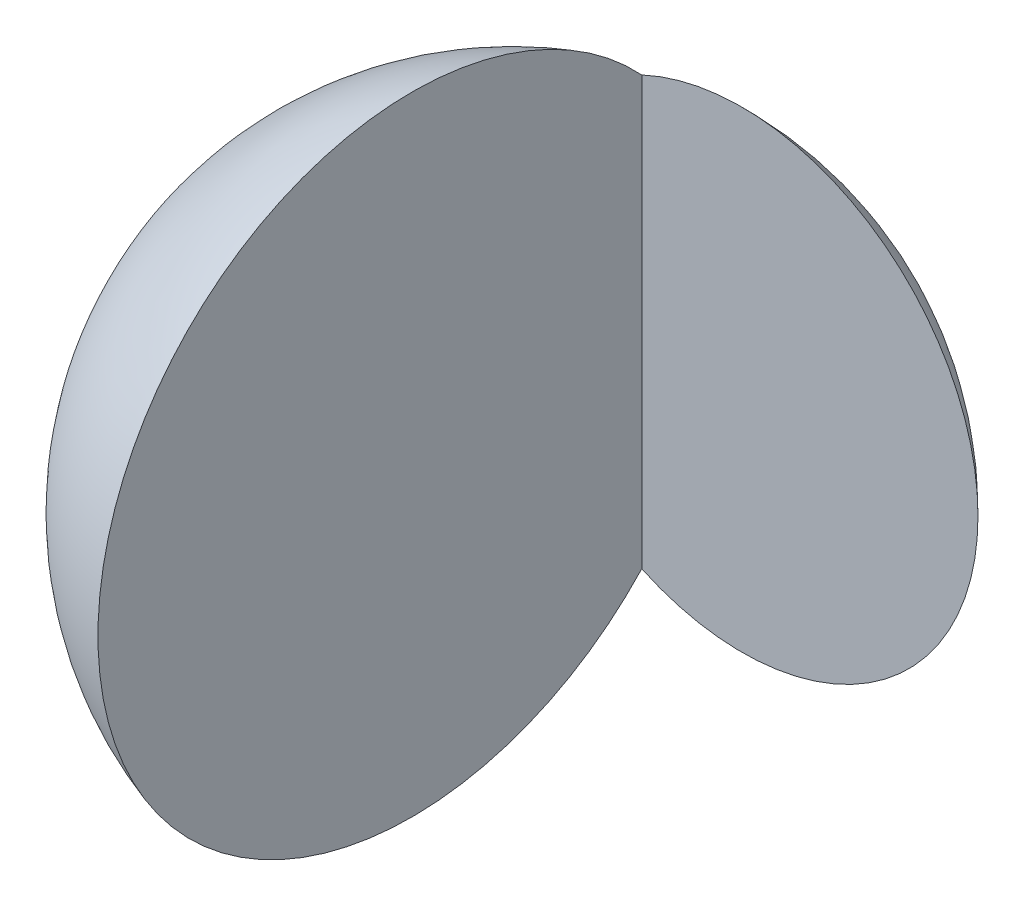
SolidWorks part; units mm, degrees
ref_plane "Front Plane" through (0, 0, 0) normal (0, 0, 1) x (1, 0, 0)
ref_plane "Top Plane" through (0, 0, 0) normal (0, 1, 0) x (1, 0, 0)
ref_plane "Right Plane" through (0, 0, 0) normal (1, 0, 0) x (0, 0, -1)
sketch "Sketch1" plane through (0, 0, 0) normal (0, 1, 0) x (1, 0, 0)
  line L0 (-27.6247, 0) -> (27.6247, 0)
  arc A0 (-27.6247, 0) -> (27.6247, 0) centre (0, 0) cw
revolve "Revolve1" add sketch "Sketch1" angle 360 about L0
sketch "Sketch2" plane through (0, 0, 0) normal (0, 1, 0) x (1, 0, 0)
  line L1 (-8.3935, 19.2696) -> (67.4999, 19.2696)
  line L2 (-8.3935, 19.2696) -> (-8.3935, -61.9644)
  line L3 (-8.3935, -61.9644) -> (67.4999, -61.9644)
  line L4 (67.4999, 19.2696) -> (67.4999, -61.9644)
extrude "Cut-Extrude1" cut sketch "Sketch2" against normal through all and the other way through all
